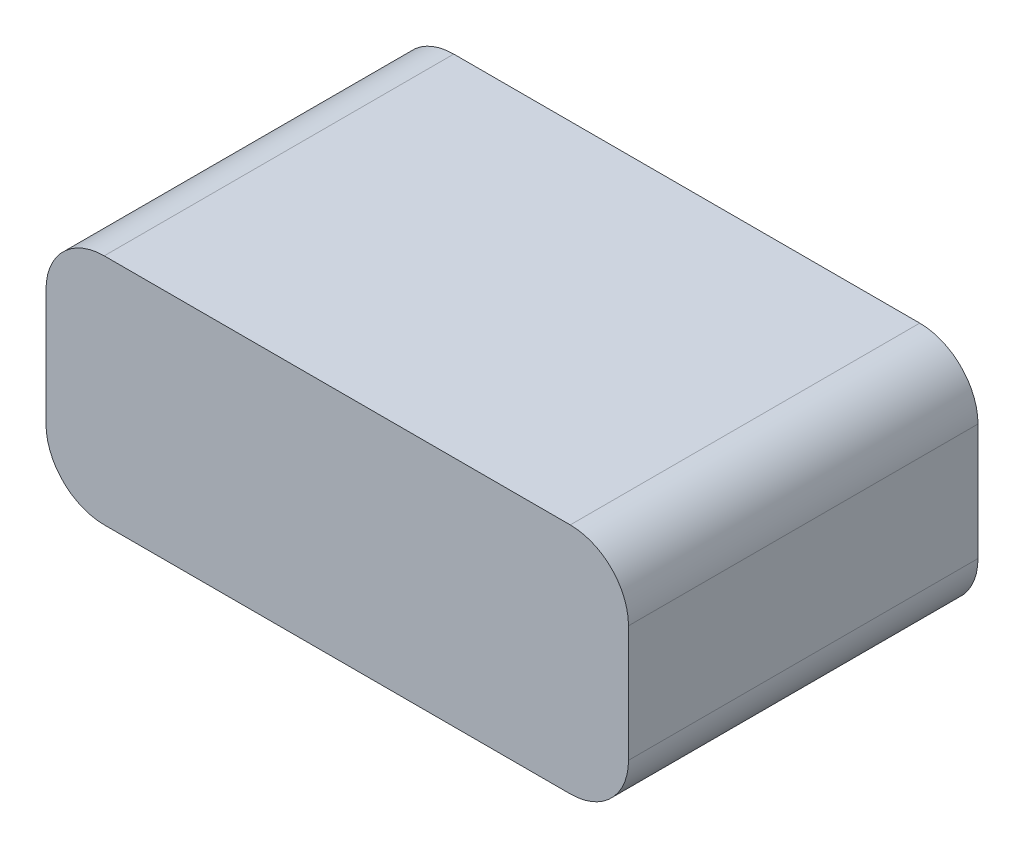
SolidWorks part; units mm, degrees
ref_plane "Front Plane" through (0, 0, 0) normal (0, 0, 1) x (1, 0, 0)
ref_plane "Top Plane" through (0, 0, 0) normal (0, 1, 0) x (1, 0, 0)
ref_plane "Right Plane" through (0, 0, 0) normal (1, 0, 0) x (0, 0, -1)
sketch "Sketch1" plane through (0, 0, 0) normal (0, 0, 1) x (1, 0, 0)
  line L0 (0, 2) -> (0, -2) construction
  line L1 (-5, 2) -> (5, 2)
  line L2 (-5, 2) -> (-5, -2)
  line L3 (-5, -2) -> (5, -2)
  line L4 (5, 2) -> (5, -2)
  dimension "D1" = 10
  dimension "D2" = 4
extrude "Boss-Extrude1" add sketch "Sketch1" along normal blind 6
fillet "Fillet1" radius 1 4 edges at (-5, -2, 3) (-5, 2, 3) (5, -2, 3) (5, 2, 3)
